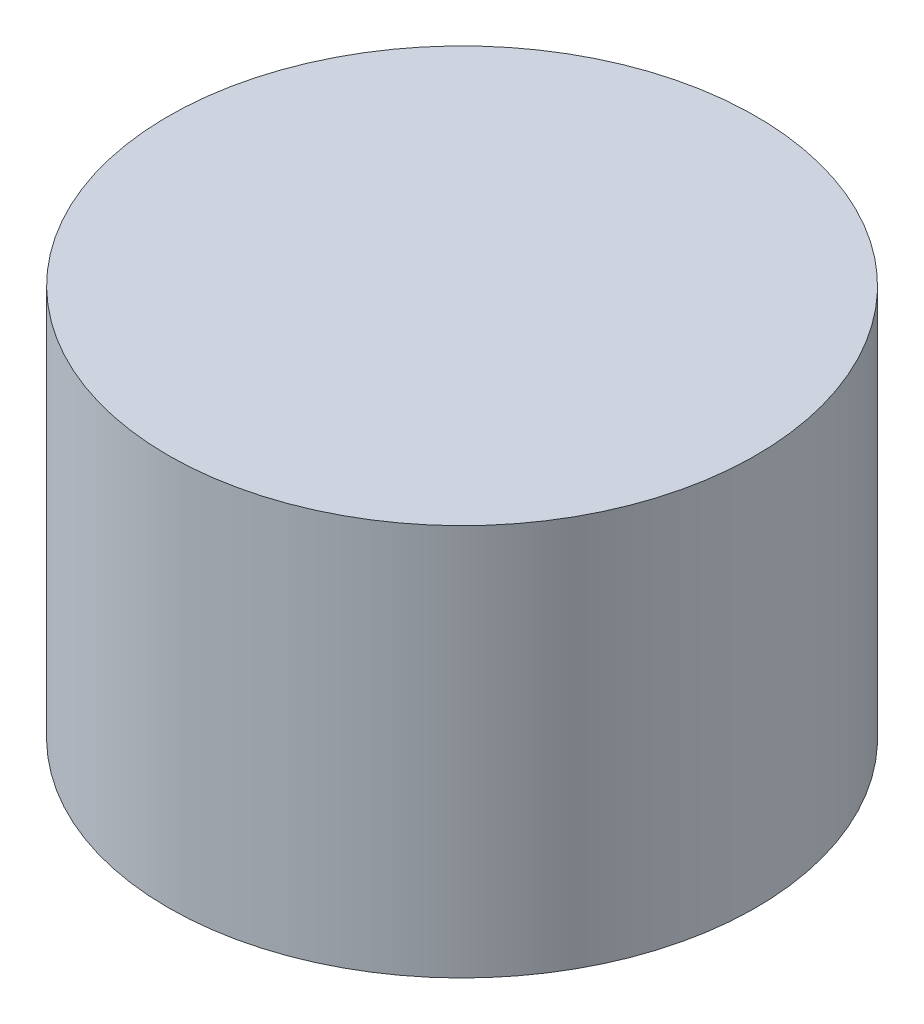
SolidWorks part; units mm, degrees
ref_plane "Front Plane" through (0, 0, 0) normal (0, 0, 1) x (1, 0, 0)
ref_plane "Top Plane" through (0, 0, 0) normal (0, 1, 0) x (1, 0, 0)
ref_plane "Right Plane" through (0, 0, 0) normal (1, 0, 0) x (0, 0, -1)
sketch "Sketch1" plane through (0, 0, 0) normal (0, 1, 0) x (1, 0, 0)
  circle A0 centre (0, 0) radius 24
extrude "Motor" add sketch "Sketch1" along normal blind 32
